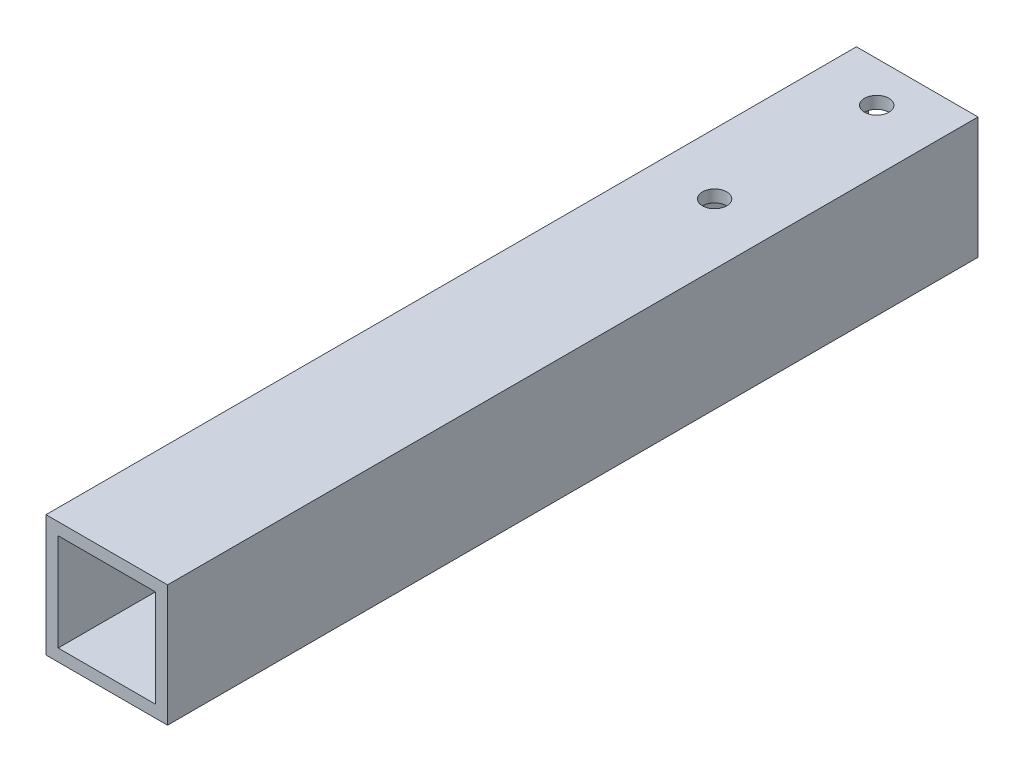
SolidWorks part; units mm, degrees
ref_plane "Plan de face" through (0, 0, 0) normal (0, 0, 1) x (1, 0, 0)
ref_plane "Plan de dessus" through (0, 0, 0) normal (0, 1, 0) x (1, 0, 0)
ref_plane "Plan de droite" through (0, 0, 0) normal (1, 0, 0) x (0, 0, -1)
sketch "Esquisse1" plane through (0, 0, 0) normal (0, 0, 1) x (1, 0, 0)
  line L1 (-7.5, -7.5) -> (7.5, -7.5)
  line L2 (-7.5, -7.5) -> (-7.5, 7.5)
  line L3 (-7.5, 7.5) -> (7.5, 7.5)
  line L4 (7.5, -7.5) -> (7.5, 7.5)
  line L5 (-7.5, -7.5) -> (7.5, 7.5) construction
  line L6 (-7.5, 7.5) -> (7.5, -7.5) construction
  point P0 (0, 0)
  dimension "D1" = 15
  dimension "D2" = 15
extrude "Extrusion1" add sketch "Esquisse1" along normal blind 100
sketch "Esquisse2" plane through (0, 0, 100) normal (0, 0, 1) x (1, 0, 0)
  line L0 (7.5, 7.5) -> (-7.5, 7.5) construction
  line L1 (-6, -6) -> (6, -6)
  line L2 (-6, -6) -> (-6, 6)
  line L3 (-6, 6) -> (6, 6)
  line L4 (6, -6) -> (6, 6)
  line L5 (-6, -6) -> (6, 6) construction
  line L6 (-6, 6) -> (6, -6) construction
  line L7 (7.5, -7.5) -> (7.5, 7.5) construction
  point P0 (0, 0)
  dimension "D1" = 1.5
  dimension "D2" = 1.5
extrude "Extrusion2" cut sketch "Esquisse2" against normal through all
sketch "Esquisse3" plane through (0, 7.5, 0) normal (0, 1, 0) x (1, 0, 0)
  line L0 (-7.5, -100) -> (-7.5, 0) construction
  line L1 (7.5, 0) -> (-7.5, 0) construction
  circle A0 centre (0, -5) radius 1.5
  dimension "D1" = 3
  dimension "D2" = 7.5
  dimension "D3" = 5
extrude "Extrusion3" cut sketch "Esquisse3" against normal through all
pattern_linear "Répétition linéaire1" count 2 spacing 20 along (0, 0, 1) of "Extrusion3"
